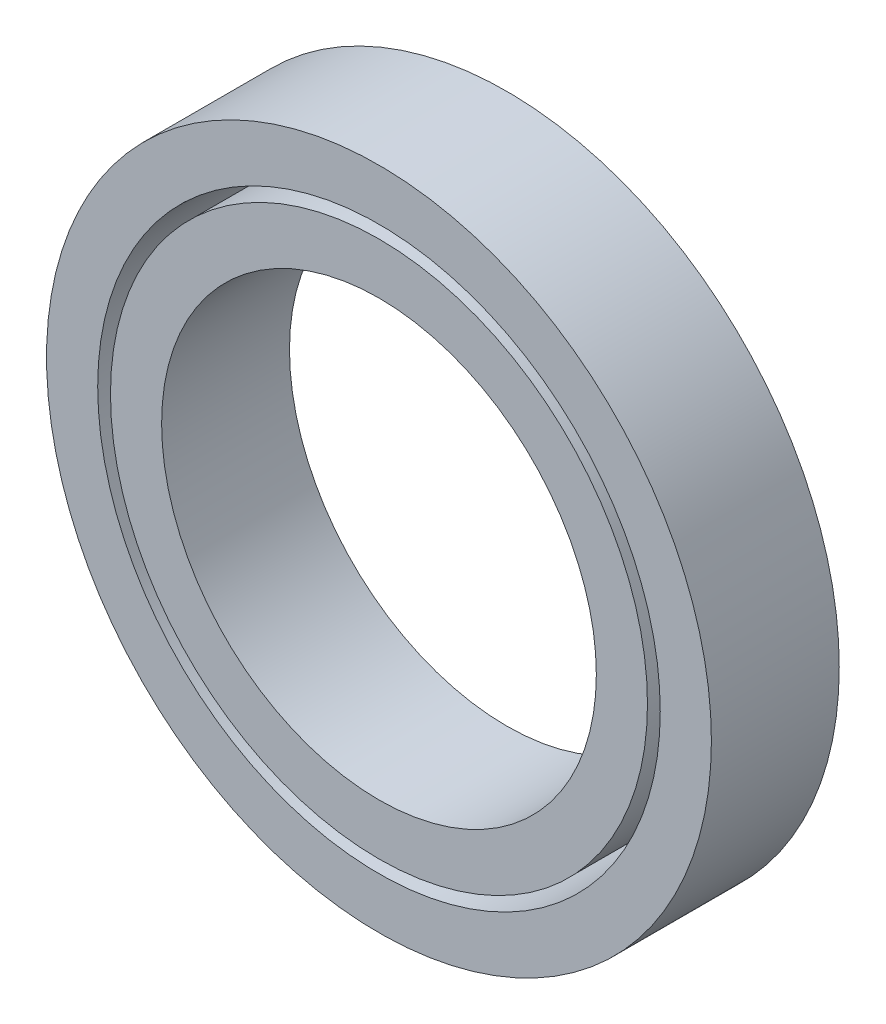
SolidWorks part; units mm, degrees
ref_plane "Plan de face" through (0, 0, 0) normal (0, 0, 1) x (1, 0, 0)
ref_plane "Plan de dessus" through (0, 0, 0) normal (0, 1, 0) x (1, 0, 0)
ref_plane "Plan de droite" through (0, 0, 0) normal (1, 0, 0) x (0, 0, -1)
sketch "Esquisse1" plane through (0, 0, 0) normal (0, 1, 0) x (1, 0, 0)
  line L0 (0, -6.6223) -> (0, 9.1695) construction
  line L1 (8.5, 0) -> (10.5, 0)
  line L2 (8.5, 0) -> (8.5, 5)
  line L3 (8.5, 5) -> (10.5, 5)
  line L4 (10.5, 0) -> (10.5, 5)
  line L5 (11, 0) -> (13, 0)
  line L6 (11, 0) -> (11, 5)
  line L7 (11, 5) -> (13, 5)
  line L8 (13, 0) -> (13, 5)
  dimension "D1" = 8.5
  dimension "D2" = 13
  dimension "D3" = 5
  dimension "D4" = 5
  dimension "D5" = 2
  dimension "D6" = 2
revolve "Révolution1" add sketch "Esquisse1" angle 360 about L0
